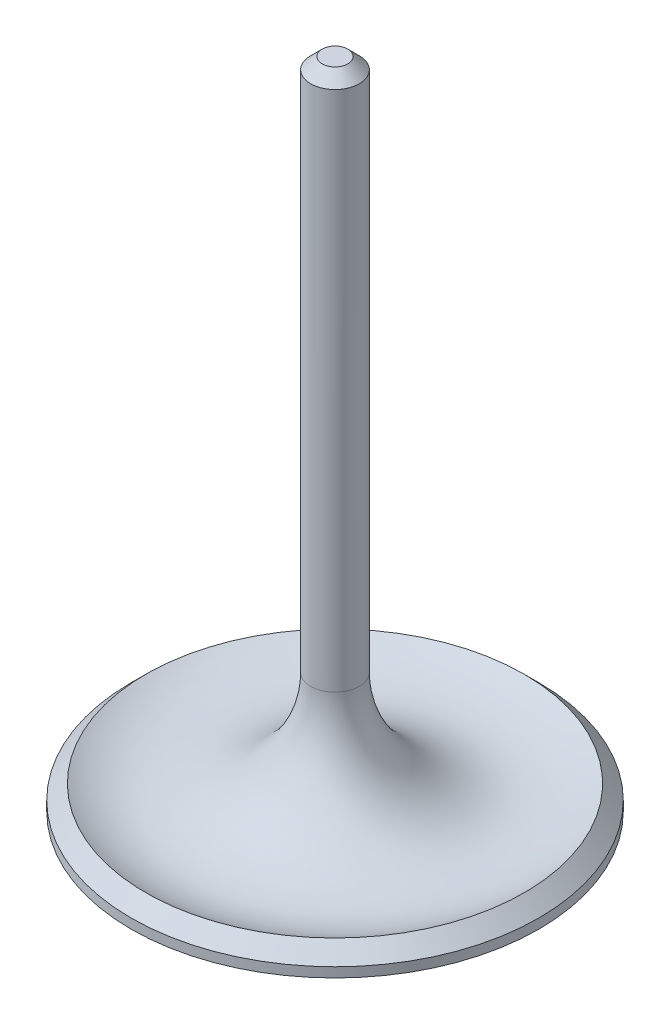
SolidWorks part; units mm, degrees
ref_plane "Front Plane" through (0, 0, 0) normal (0, 0, 1) x (1, 0, 0)
ref_plane "Top Plane" through (0, 0, 0) normal (0, 1, 0) x (1, 0, 0)
ref_plane "Right Plane" through (0, 0, 0) normal (1, 0, 0) x (0, 0, -1)
sketch "Sketch1" plane through (0, 0, 0) normal (0, 0, 1) x (1, 0, 0)
  line L0 (0, 0) -> (0, 85.55)
  line L1 (0, 85.55) -> (3.18, 85.55)
  line L2 (3.18, 85.55) -> (3.18, 15.7661)
  line L3 (0, 0) -> (26.67, 0)
  line L4 (26.67, 0) -> (26.67, 1.27)
  line L5 (26.67, 1.27) -> (24.76, 3.18)
  arc A1 (3.18, 15.7661) -> (24.76, 3.18) centre (17.6403, 15.7661) ccw
  dimension "D7" = 14.4603
  dimension "D1" = 26.67
  dimension "D2" = 1.27
  dimension "D3" = 3.18
  dimension "D4" = 45
  dimension "D5" = 85.55
  dimension "D6" = 3.18
revolve "Revolve1" add sketch "Sketch1" angle 360 about L0
chamfer "Chamfer1" distance 1.5 angle 45 1 edges at (0, 85.55, -3.18)
